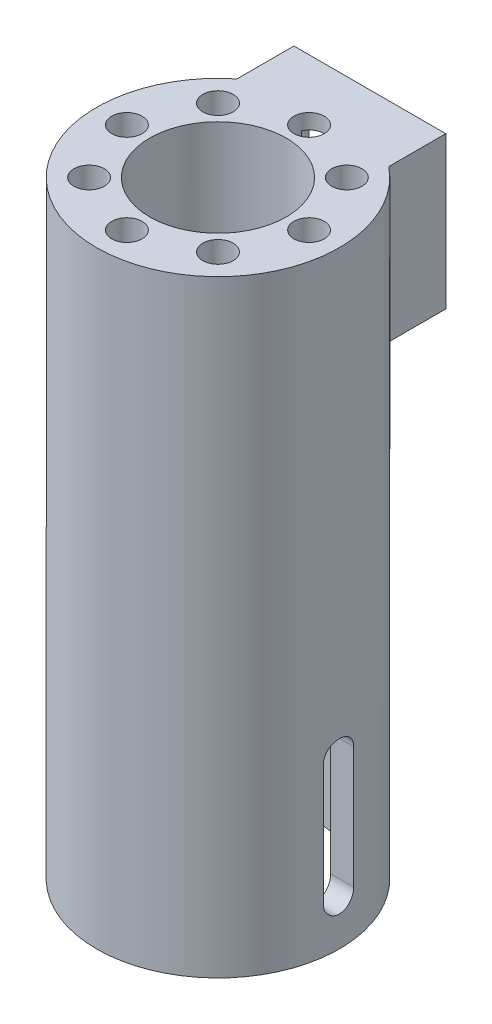
SolidWorks part; units mm, degrees
ref_plane "Front Plane" through (0, 0, 0) normal (0, 0, 1) x (1, 0, 0)
ref_plane "Top Plane" through (0, 0, 0) normal (0, 1, 0) x (1, 0, 0)
ref_plane "Right Plane" through (0, 0, 0) normal (1, 0, 0) x (0, 0, -1)
sketch "Sketch1" plane through (0, 0, 0) normal (0, 1, 0) x (1, 0, 0)
  line L1 (0, 50) -> (-25, 50)
  line L2 (0, 50) -> (25, 50)
  line L3 (-25, 50) -> (-25, 31.225)
  line L4 (25, 50) -> (25, 31.225)
  arc A0 (-25, 31.225) -> (25, 31.225) centre (0, 0) ccw
  dimension "D1" = 80
  dimension "D2" = 50
  dimension "D3" = 50
extrude "Boss-Extrude4" add sketch "Sketch1" against normal blind 200
sketch "Sketch5" plane through (0, -200, 0) normal (0, -1, 0) x (1, 0, 0)
  line L0 (-25, -31.225) -> (-25, -50)
  line L1 (-25, -50) -> (25, -50)
  line L2 (25, -50) -> (25, -31.225)
  arc A0 (-25, -31.225) -> (25, -31.225) centre (0, 0) ccw
extrude "Cut-Extrude3" cut sketch "Sketch5" against normal blind 150
sketch "Sketch6" plane through (0, 0, 0) normal (0, 1, 0) x (1, 0, 0)
  circle A0 centre (0, 0) radius 22.5
  dimension "D1" = 45
extrude "Cut-Extrude5" cut sketch "Sketch6" against normal blind 120
sketch "Sketch7" plane through (0, -200, 0) normal (0, -1, 0) x (1, 0, 0)
  circle A0 centre (0, 0) radius 32.5
  dimension "D1" = 65
extrude "Cut-Extrude6" cut sketch "Sketch7" against normal blind 80
fillet "Fillet2" radius 4 1 edges at (0, -120, -32.5)
sketch "Sketch8" plane through (0, 0, -50) normal (0, 0, -1) x (-1, 0, 0)
  line L3 (20, -5) -> (-20, -5)
  line L4 (20, -5) -> (20, -45)
  line L5 (20, -45) -> (-20, -45)
  line L6 (-20, -5) -> (-20, -45)
  line L7 (20, -5) -> (-20, -45) construction
  line L8 (20, -45) -> (-20, -5) construction
  point P5 (0, -25)
  dimension "D1" = 40
extrude "Cut-Extrude7" cut sketch "Sketch8" against normal blind 18
fillet "Fillet3" radius 5 4 edges at (20, -45, -41) (20, -5, -41) (-20, -5, -41) (-20, -45, -41)
sketch "Sketch10" plane through (0, 0, 0) normal (1, 0, 0) x (0, 0, -1)
  line L2 (5, -185) -> (-5, -185)
  line L3 (5, -145) -> (-5, -145)
  line L4 (5, -145) -> (5, -185)
  line L5 (-5, -185) -> (-5, -145)
  arc A0 (5, -185) -> (-5, -185) centre (0, -185) cw
  arc A1 (5, -145) -> (-5, -145) centre (0, -145) ccw
  point P8 (0, -185)
  point P12 (0, -145)
  dimension "D3" = 5
  dimension "D4" = 5
  dimension "D1" = 40
extrude "Cut-Extrude9" cut sketch "Sketch10" along normal blind 69 contours L5 L2 L4 L3 | L3 A1 | A0 L2
sketch "Sketch11" plane through (0, 0, 0) normal (0, 1, 0) x (1, 0, 0)
  circle A0 centre (30, 0) radius 5
  circle A1 centre (21.2132, -21.2132) radius 5
  circle A2 centre (0, -30) radius 5
  circle A3 centre (-21.2132, -21.2132) radius 5
  circle A4 centre (-30, 0) radius 5
  circle A5 centre (-21.2132, 21.2132) radius 5
  circle A6 centre (0, 30) radius 5
  circle A7 centre (21.2132, 21.2132) radius 5
  point P20 (0, 0)
  dimension "D2" = 10
  dimension "D1" = 8
extrude "Cut-Extrude10" cut sketch "Sketch11" against normal blind 10
